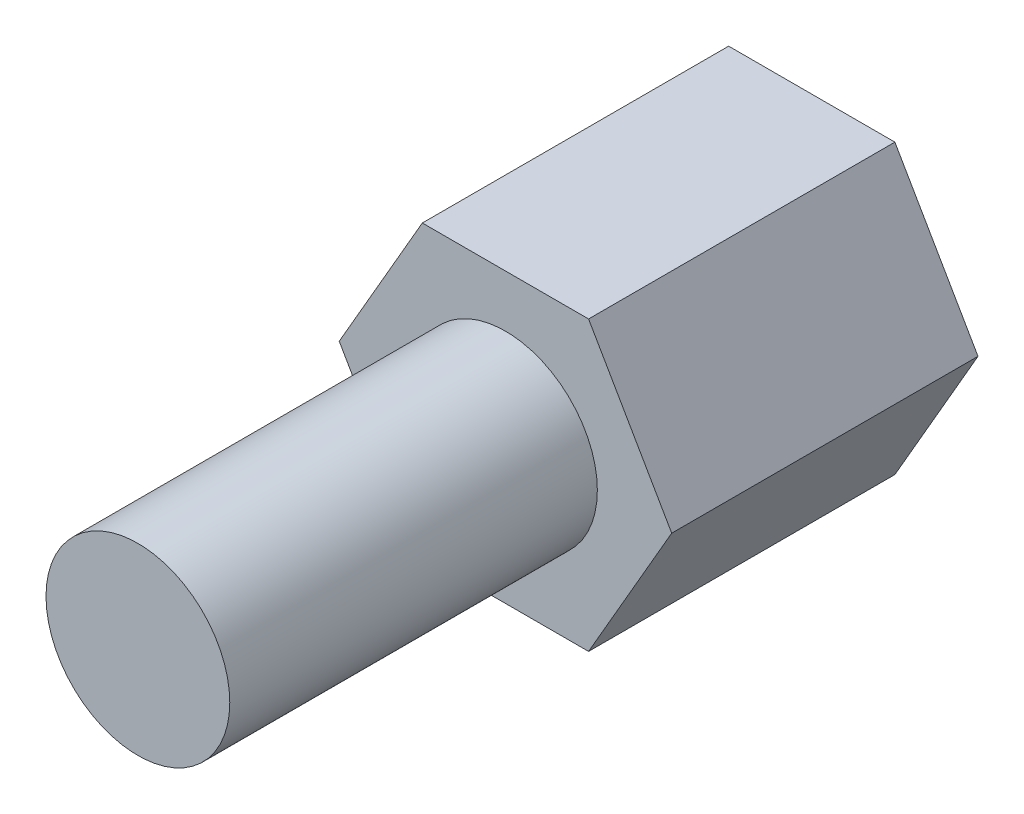
SolidWorks part; units mm, degrees
ref_plane "前视基准面" through (0, 0, 0) normal (0, 0, 1) x (1, 0, 0)
ref_plane "上视基准面" through (0, 0, 0) normal (0, 1, 0) x (1, 0, 0)
ref_plane "右视基准面" through (0, 0, 0) normal (1, 0, 0) x (0, 0, -1)
sketch "草图1" plane through (0, 0, 0) normal (0, 0, 1) x (1, 0, 0)
  line L1 (2.7135, 0) -> (1.3568, 2.35)
  line L2 (1.3568, 2.35) -> (-1.3568, 2.35)
  line L3 (-1.3568, 2.35) -> (-2.7135, 0)
  line L4 (-2.7135, 0) -> (-1.3568, -2.35)
  line L5 (-1.3568, -2.35) -> (1.3568, -2.35)
  line L6 (1.3568, -2.35) -> (2.7135, 0)
  circle A0 centre (0, 0) radius 2.35 construction
  point P1 (-2.0352, -1.175)
  dimension "D1" = 4.7
extrude "凸台-拉伸1" add sketch "草图1" along normal blind 5
sketch "草图2" plane through (0, 0, 5) normal (0, 0, 1) x (1, 0, 0)
  circle A0 centre (0, 0) radius 1.5
  dimension "D1" = 3
extrude "凸台-拉伸2" add sketch "草图2" along normal blind 6
sketch "草图3" plane through (0, 0, 0) normal (0, 0, -1) x (-1, 0, 0)
  circle A0 centre (0, 0) radius 1.5
  dimension "D1" = 3
extrude "切除-拉伸1" cut sketch "草图3" against normal up to surface (5 mm away) up to face at (1.5, 0, 5)
